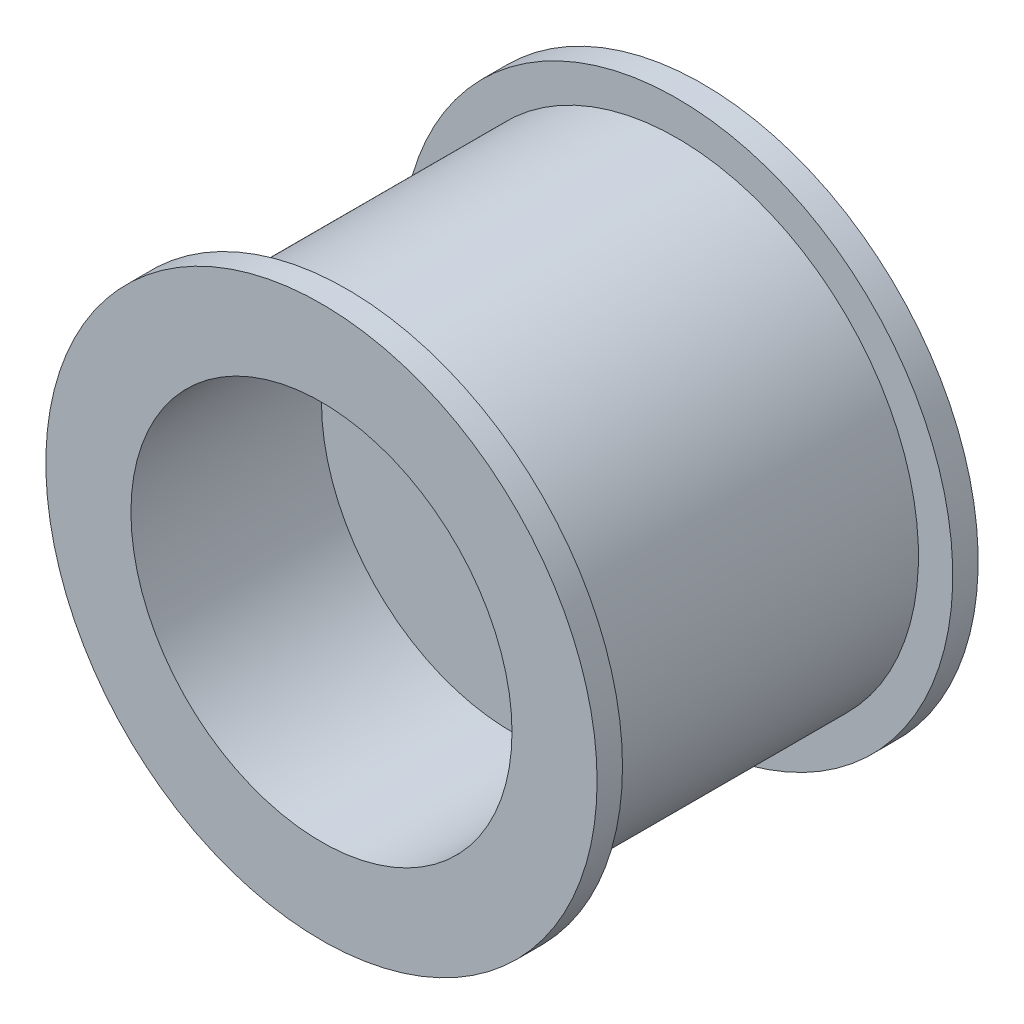
SolidWorks part; units mm, degrees
material "Aleación 1060"
ref_plane "Alzado" through (0, 0, 0) normal (0, 0, 1) x (1, 0, 0)
ref_plane "Planta" through (0, 0, 0) normal (0, 1, 0) x (1, 0, 0)
ref_plane "Vista lateral" through (0, 0, 0) normal (1, 0, 0) x (0, 0, -1)
sketch "Croquis2" plane through (0, 0, 0) normal (0, 0, 1) x (1, 0, 0)
  circle A1 centre (0, 0) radius 19
  dimension "D1" = 38
extrude "Saliente-Extruir1" add sketch "Croquis2" along normal blind 26
sketch "Croquis3" plane through (0, 0, 26) normal (0, 0, 1) x (1, 0, 0)
  circle A0 centre (0, 0) radius 21.7
  dimension "D1" = 43.4
extrude "Saliente-Extruir2" add sketch "Croquis3" along normal blind 2 from offset 0
sketch "Croquis4" plane through (0, 0, 0) normal (0, 0, -1) x (-1, 0, 0)
  circle A0 centre (0, 0) radius 21.7
  dimension "D1" = 43.4
extrude "Saliente-Extruir3" add sketch "Croquis4" along normal blind 2 contours A0
sketch "Croquis5" plane through (0, 0, 28) normal (0, 0, 1) x (1, 0, 0)
  circle A0 centre (0, 0) radius 15
  dimension "D1" = 30
extrude "Cortar-Extruir1" cut sketch "Croquis5" against normal blind 15
sketch "Croquis6" plane through (0, 0, 13) normal (0, 0, 1) x (1, 0, 0)
  circle A0 centre (0, 0) radius 3
  dimension "D1" = 6
extrude "Cortar-Extruir2" cut sketch "Croquis6" against normal through all
sketch "Croquis7" plane through (0, 0, -2) normal (0, 0, -1) x (-1, 0, 0)
  line L0 (0, 0) -> (0, 12.5) construction
  circle A0 centre (0, 12.5) radius 3
  circle A1 centre (0, 0) radius 12.5 construction
  circle A2 centre (0, 0) radius 3 construction
  circle A3 centre (10.8253, 6.25) radius 3
  circle A4 centre (10.8253, -6.25) radius 3
  circle A5 centre (0, -12.5) radius 3
  circle A6 centre (-10.8253, -6.25) radius 3
  circle A7 centre (-10.8253, 6.25) radius 3
  dimension "D1" = 6
  dimension "D2" = 12.5
  dimension "D3" = 6
extrude "Cortar-Extruir3" cut sketch "Croquis7" against normal blind 10 contours A0 | A3 | A4 | A5 | A6 | A7
